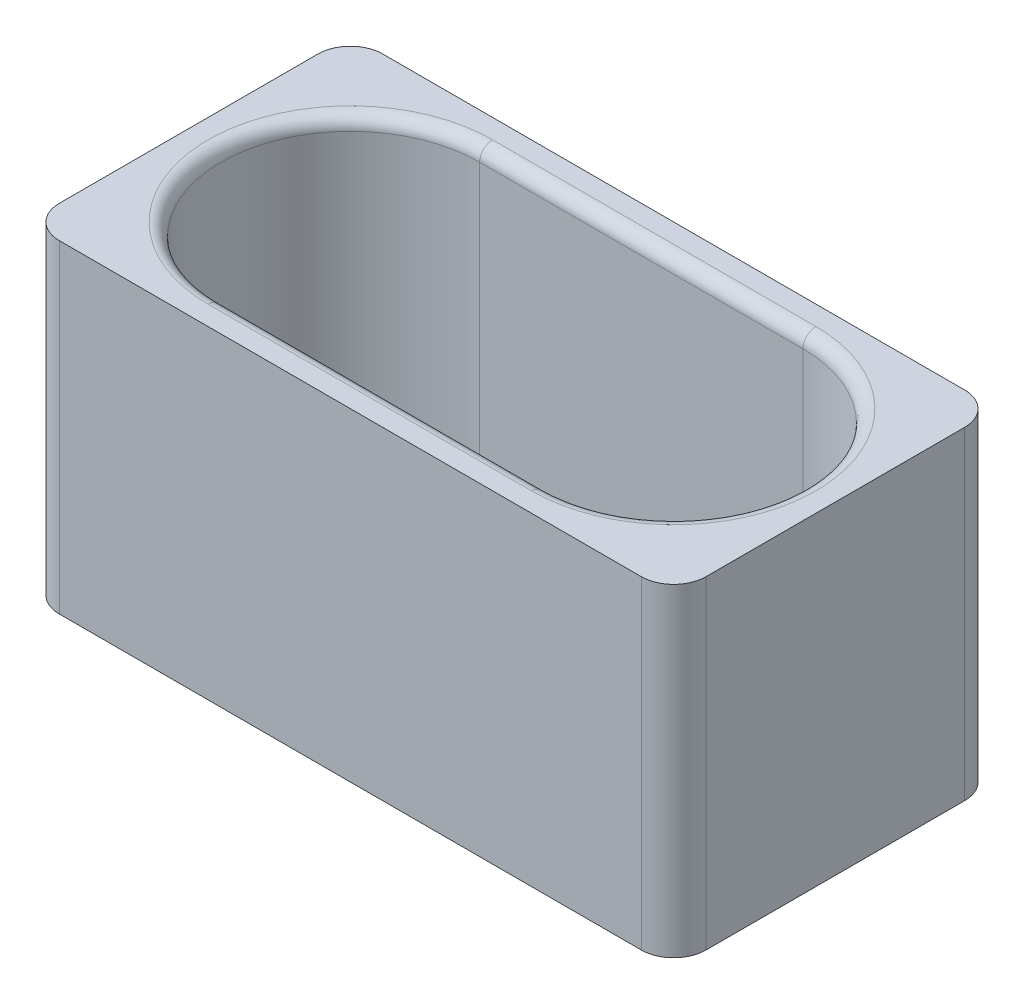
SolidWorks part; units mm, degrees
material "Cast Alloy Steel"
ref_plane "Front Plane" through (0, 0, 0) normal (0, 0, 1) x (1, 0, 0)
ref_plane "Top Plane" through (0, 0, 0) normal (0, 1, 0) x (1, 0, 0)
ref_plane "Right Plane" through (0, 0, 0) normal (1, 0, 0) x (0, 0, -1)
sketch "Sketch1" plane through (0, 0, 0) normal (0, 1, 0) x (1, 0, 0)
  line L1 (-50, -25) -> (50, -25)
  line L2 (-50, -25) -> (-50, 25)
  line L3 (-50, 25) -> (50, 25)
  line L4 (50, -25) -> (50, 25)
  line L5 (-50, -25) -> (50, 25) construction
  line L6 (-50, 25) -> (50, -25) construction
  point P0 (0, 0)
  dimension "D1" = 50
  dimension "D2" = 100
extrude "Boss-Extrude1" add sketch "Sketch1" along normal blind 50
fillet "Fillet1" radius 5 4 edges at (50, 25, -25) (50, 25, 25) (-50, 25, -25) (-50, 25, 25)
sketch "Sketch2" plane through (0, 0, 0) normal (0, -1, 0) x (1, 0, 0)
  line L0 (-54.7004, 0) -> (56.3445, 0) construction
  line L1 (50, 20) -> (50, -20) construction
  circle A0 centre (-25, 0) radius 2.5
  circle A1 centre (25, 0) radius 2.5
  dimension "D1" = 5
  dimension "D2" = 25
  dimension "D3" = 50
extrude "Boss-Extrude2" add sketch "Sketch2" along normal blind 5
chamfer "Chamfer1" distance 1 angle 45 2 edges at (25, -5, -2.5) (-25, -5, -2.5)
sketch "Sketch3" plane through (0, 50, 0) normal (0, 1, 0) x (1, 0, 0)
  line L0 (-25, 0) -> (25, 0) construction
  line L1 (-25, 20) -> (25, 20)
  line L2 (-25, -20) -> (25, -20)
  line L3 (45, 25) -> (-45, 25) construction
  line L4 (-50, 20) -> (-50, -20) construction
  arc A0 (-25, 20) -> (-25, -20) centre (-25, 0) ccw
  arc A1 (25, -20) -> (25, 20) centre (25, 0) ccw
  point P2 (0, 0)
  dimension "D2" = 25
  dimension "D1" = 5
extrude "Cut-Extrude1" cut sketch "Sketch3" against normal offset from surface (45 mm away) 5 up to face at (25, 0, -2.5)
fillet "Fillet2" radius 2 8 edges at (0, 5, -20) (45, 5, 0) (0, 5, 20) (0, 50, -20) (45, 50, 0) (0, 50, 20) (-45, 5, 0) (-45, 50, 0)
